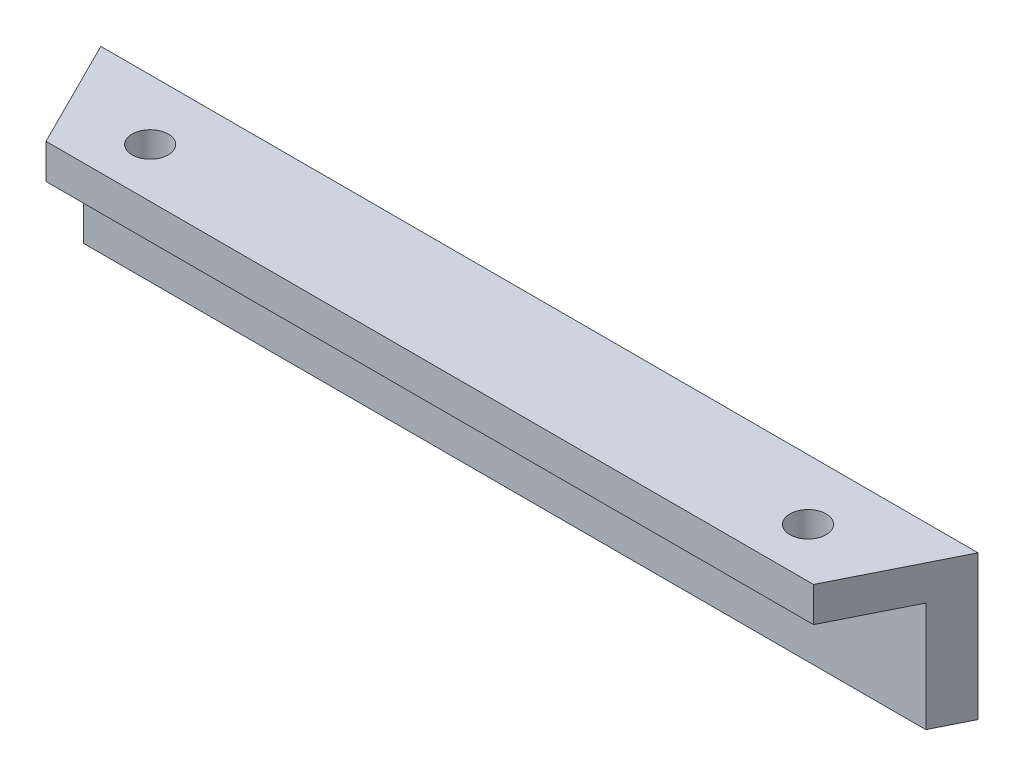
SolidWorks part; units mm, degrees
ref_plane "Front Plane" through (0, 0, 0) normal (0, 0, 1) x (1, 0, 0)
ref_plane "Top Plane" through (0, 0, 0) normal (0, 1, 0) x (1, 0, 0)
ref_plane "Right Plane" through (0, 0, 0) normal (1, 0, 0) x (0, 0, -1)
sketch "Sketch1" plane through (0, 0, 0) normal (0, 1, 0) x (1, 0, 0)
  line L0 (-21.9971, 0) -> (58.0029, 0)
  line L1 (58.0029, 0) -> (53.0029, -10)
  line L2 (53.0029, -10) -> (-16.9971, -10)
  line L3 (-16.9971, -10) -> (-21.9971, 0)
  line L4 (18.0029, 0) -> (18.0029, -10) construction
  circle A0 centre (-11.9971, -5.5) radius 1.65
  circle A1 centre (48.0029, -5.5) radius 1.65
  point P3 (18.0029, 0)
  dimension "D5" = 3.3
  dimension "D1" = 80
  dimension "D2" = 70
  dimension "D3" = 10
  dimension "D4" = 30
  dimension "D6" = 5.5
extrude "Boss-Extrude1" add sketch "Sketch1" along normal blind 3.175
sketch "Sketch2" plane through (0, 0, 0) normal (0, -1, 0) x (1, 0, 0)
  line L0 (58.0029, 0) -> (56.4154, 3.175)
  line L1 (53.0029, 10) -> (58.0029, 0) construction
  line L2 (56.4154, 3.175) -> (-20.4096, 3.175)
  line L3 (-21.9971, 0) -> (-16.9971, 10) construction
  line L4 (-20.4096, 3.175) -> (-21.9971, 0)
  line L5 (-21.9971, 0) -> (58.0029, 0)
  dimension "D1" = 3.175
extrude "Boss-Extrude2" add sketch "Sketch2" along normal blind 10
